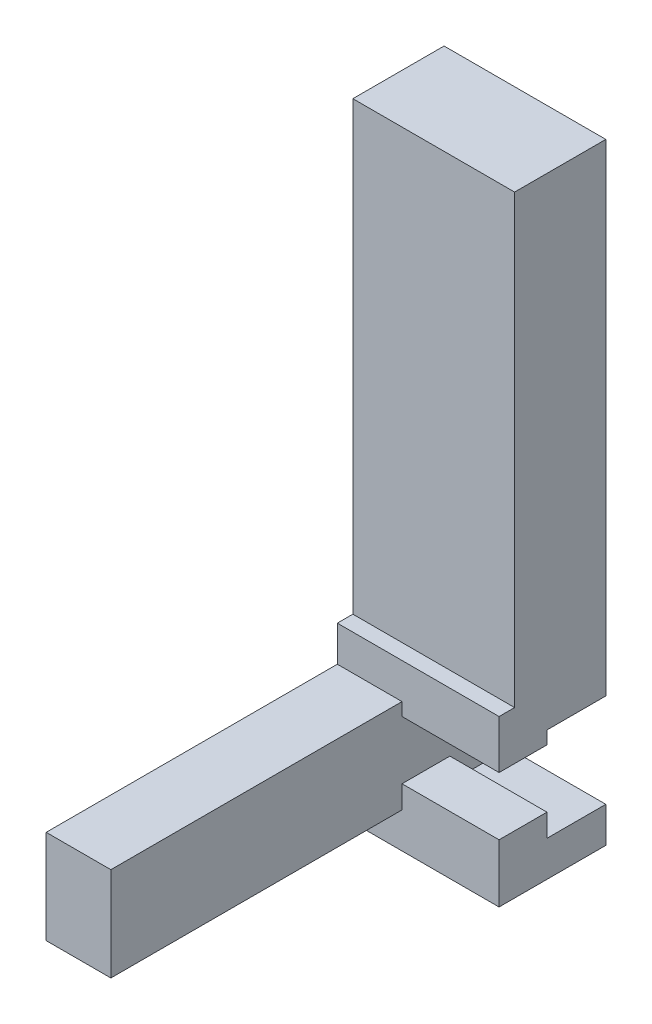
SolidWorks part; units mm, degrees
ref_plane "前视基准面" through (0, 0, 0) normal (0, 0, 1) x (1, 0, 0)
ref_plane "上视基准面" through (0, 0, 0) normal (0, 1, 0) x (1, 0, 0)
ref_plane "右视基准面" through (0, 0, 0) normal (1, 0, 0) x (0, 0, -1)
other "Configuration Table"
sketch "草图1" plane through (0, 0, 0) normal (0, 1, 0) x (1, 0, 0)
  line L1 (-1, -6) -> (1, -6)
  line L2 (-1, -6) -> (-1, 6)
  line L3 (-1, 6) -> (1, 6)
  line L4 (1, -6) -> (1, 6)
  line L5 (-1, -6) -> (1, 6) construction
  line L6 (-1, 6) -> (1, -6) construction
  point P0 (0, 0)
  dimension "D1" = 2
  dimension "D2" = 12
extrude "凸台-拉伸1" add sketch "草图1" along normal blind 2.9
sketch "草图2" plane through (1, 0, 0) normal (1, 0, 0) x (0, 0, -1)
  line L0 (6, 2.9) -> (6, 0) construction
  line L1 (2.7, 2.5) -> (4.18, 2.5)
  line L2 (2.7, 2.5) -> (2.7, 4)
  line L3 (2.7, 4) -> (4.18, 4)
  line L4 (4.18, 2.5) -> (4.18, 4)
  line L5 (-6, 2.9) -> (6, 2.9) construction
  line L6 (-6, 0) -> (6, 0) construction
  line L7 (4.18, 0.7) -> (2.7, 0.7)
  line L8 (4.18, 0.7) -> (4.18, -1.1)
  line L9 (4.18, -1.1) -> (2.7, -1.1)
  line L10 (2.7, 0.7) -> (2.7, -1.1)
  dimension "D1" = 1.82
  dimension "D2" = 0.4
  dimension "D3" = 1.1
  dimension "D4" = 0.7
  dimension "D5" = 1.1
  dimension "D6" = 1.48
extrude "凸台-拉伸2" add sketch "草图2" against normal up to surface (5 mm away) from offset 3
sketch "草图3" plane through (-1, 0, 0) normal (-1, 0, 0) x (0, 0, 1)
  line L1 (-2.7, 2.9) -> (6.3, 2.9)
  line L2 (-2.7, 2.9) -> (-2.7, 0)
  line L3 (-2.7, 0) -> (6.3, 0)
  line L4 (6.3, 2.9) -> (6.3, 0)
  line L10 (-2.7, 2.9) -> (6, 2.9) construction
  line L11 (-2.7, 0) -> (6, 0) construction
  line L12 (-2.7, 2.9) -> (-2.7, 4) construction
  dimension "D3" = 9
extrude "凸台-拉伸3" add sketch "草图3" against normal blind 2
sketch "草图4" plane through (0, 4, 0) normal (0, 1, 0) x (1, 0, 0)
  line L0 (-1, 4.18) -> (4, 4.18) construction
  line L1 (-1, 5.18) -> (1, 5.18)
  line L2 (-1, 5.18) -> (-1, 3.18)
  line L3 (-1, 3.18) -> (1, 3.18)
  line L4 (1, 5.18) -> (1, 3.18)
  line L5 (-1, 6) -> (-1, 4.18) construction
  line L6 (1, 4.18) -> (1, 6) construction
  dimension "D1" = 1
  dimension "D2" = 1
extrude "凸台-拉伸4" add sketch "草图4" along normal blind 18.9 from surface at -5.1 starting at face at (1.5, -1.1, -3.44)
sketch "草图5" plane through (1, 0, 0) normal (1, 0, 0) x (0, 0, -1)
  line L0 (-6.3, 0) -> (2.7, 0) construction
  line L1 (3.18, 17.8) -> (6, 17.8)
  line L2 (3.18, 17.8) -> (3.18, 2.9)
  line L3 (3.18, 2.9) -> (6, 2.9)
  line L4 (6, 17.8) -> (6, 2.9)
  line L5 (6, -1.1) -> (3.18, -1.1)
  line L6 (6, -1.1) -> (6, 0)
  line L7 (6, 0) -> (3.18, 0)
  line L8 (3.18, -1.1) -> (3.18, 0)
  line L9 (2.7, -1.1) -> (4.18, -1.1) construction
  point P13 (0, 0)
  point P15 (0, 0)
extrude "凸台-拉伸5" add sketch "草图5" along normal up to surface (5 mm away) from surface at -2 up to face at (4, 3.25, -3.44) starting at face at (-1, 3.7857, -2.6629)
